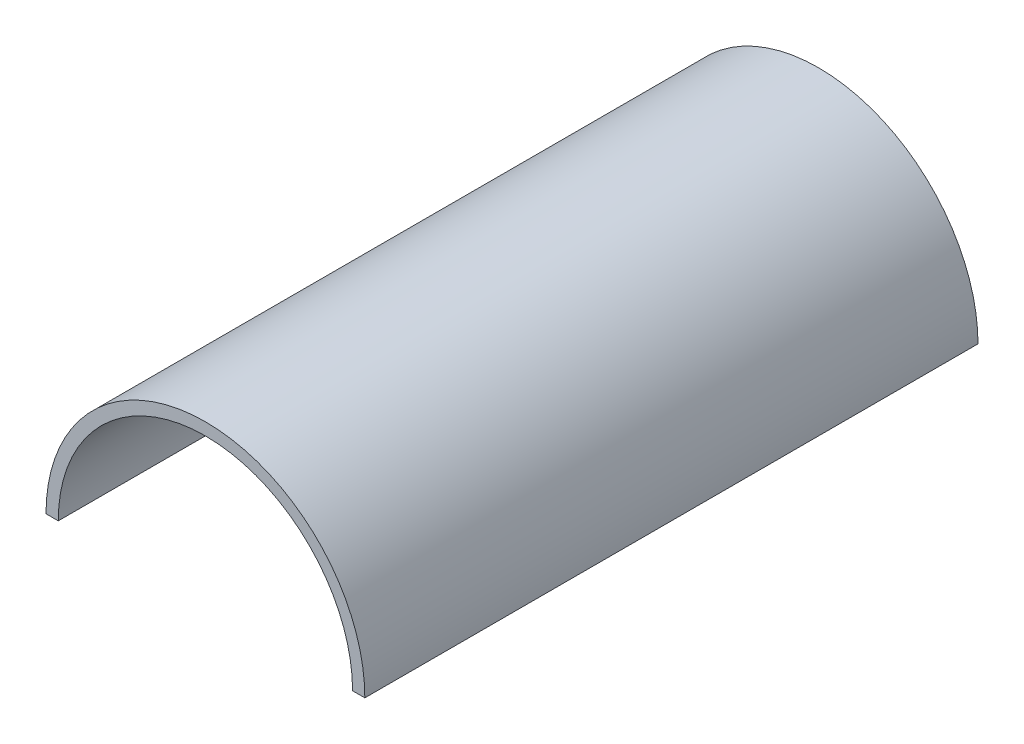
SolidWorks part; units mm, degrees
ref_plane "Plan de face" through (0, 0, 0) normal (0, 0, 1) x (1, 0, 0)
ref_plane "Plan de dessus" through (0, 0, 0) normal (0, 1, 0) x (1, 0, 0)
ref_plane "Plan de droite" through (0, 0, 0) normal (1, 0, 0) x (0, 0, -1)
sketch "Esquisse1" plane through (0, 0, 0) normal (0, 0, 1) x (1, 0, 0)
  line L0 (-26, 0) -> (-24, 0)
  line L1 (24, 0) -> (26, 0)
  arc A0 (0, 26) -> (-26, 0) centre (0, 0) ccw
  arc A1 (0, 26) -> (26, 0) centre (0, 0) cw
  arc A2 (24, 0) -> (-24, 0) centre (0, 0) ccw
extrude "Boss.-Extru.1" add sketch "Esquisse1" along normal blind 100
